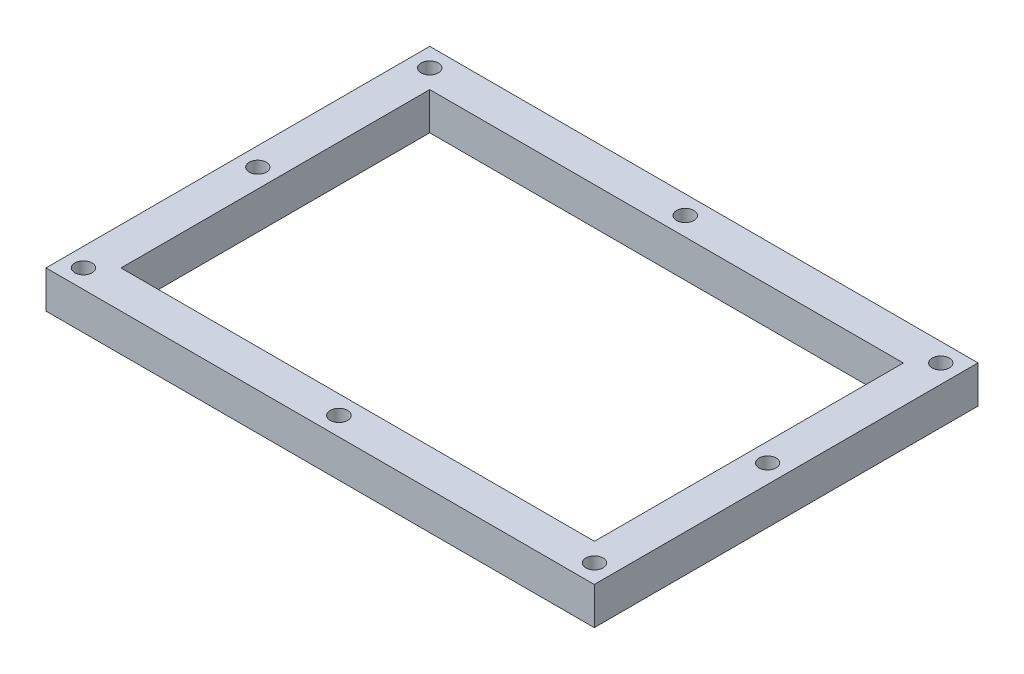
SolidWorks part; units mm, degrees
ref_plane "Спереди" through (0, 0, 0) normal (0, 0, 1) x (1, 0, 0)
ref_plane "Сверху" through (0, 0, 0) normal (0, 1, 0) x (1, 0, 0)
ref_plane "Справа" through (0, 0, 0) normal (1, 0, 0) x (0, 0, -1)
ref_plane "Плоскость4" through (0, 236.196, 0) normal (0, 1, 0) x (1, 0, 0)
sketch "Эскиз1" plane through (0, 236.196, 0) normal (0, 1, 0) x (1, 0, 0)
  line L0 (-8.441, -38.2731) -> (-8.441, -140.7731)
  line L3 (138.0105, -140.7731) -> (-8.441, -140.7731)
  line L4 (138.0105, -38.2731) -> (-8.441, -38.2731)
  line L6 (138.0105, -140.7731) -> (138.0105, -38.2731)
  line L8 (1.592, -130.7731) -> (1.559, -48.2731)
  line L9 (-8.25, -130.7731) -> (8.25, -130.7731) construction
  line L10 (1.559, -48.2731) -> (128.059, -48.2731)
  line L11 (128.059, -48.2731) -> (128.059, -130.7731)
  line L12 (128.059, -130.7731) -> (1.592, -130.7731)
  circle A0 centre (64.809, -43.2731) radius 2.3293
  circle A1 centre (-3.441, -89.1878) radius 2.3
  circle A2 centre (64.809, -135.7731) radius 2.3293
  circle A3 centre (133.059, -89.5231) radius 2.3
  circle A4 centre (-3.441, -43.2731) radius 2.3
  circle A5 centre (133.059, -43.2731) radius 2.3
  circle A6 centre (133.059, -135.7731) radius 2.3
  circle A7 centre (-3.441, -135.7731) radius 2.3
extrude "Бобышка-Вытянуть1" add sketch "Эскиз1" along normal blind 10
ref_plane "Плоскость6" through (0, 0, 38.2731) normal (0, 0, -1) x (-1, 0, 0)
ref_plane "Плоскость7" through (138.0105, 0, 0) normal (1, 0, 0) x (0, 0, -1)
ref_plane "Плоскость8" through (-8.441, 0, 0) normal (-1, 0, 0) x (0, 0, 1)
